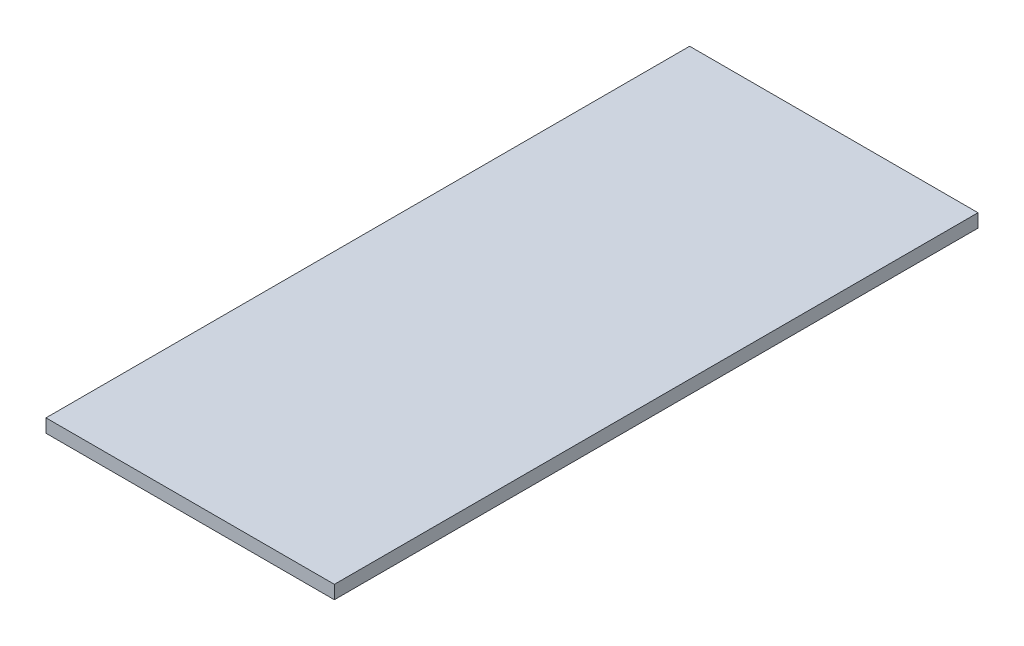
SolidWorks part; units mm, degrees
ref_plane "Front Plane" through (0, 0, 0) normal (0, 0, 1) x (1, 0, 0)
ref_plane "Top Plane" through (0, 0, 0) normal (0, 1, 0) x (1, 0, 0)
ref_plane "Right Plane" through (0, 0, 0) normal (1, 0, 0) x (0, 0, -1)
sketch "Sketch1" plane through (0, 0, 0) normal (0, 1, 0) x (1, 0, 0)
  line L1 (-86.2, 192.4) -> (86.2, 192.4)
  line L2 (-86.2, 192.4) -> (-86.2, -192.4)
  line L3 (-86.2, -192.4) -> (86.2, -192.4)
  line L4 (86.2, 192.4) -> (86.2, -192.4)
  line L5 (-86.2, 192.4) -> (86.2, -192.4) construction
  line L6 (-86.2, -192.4) -> (86.2, 192.4) construction
  point P0 (0, 0)
  dimension "D1" = 384.8
  dimension "D2" = 172.4
extrude "Boss-Extrude1" add sketch "Sketch1" along normal mid plane 8
